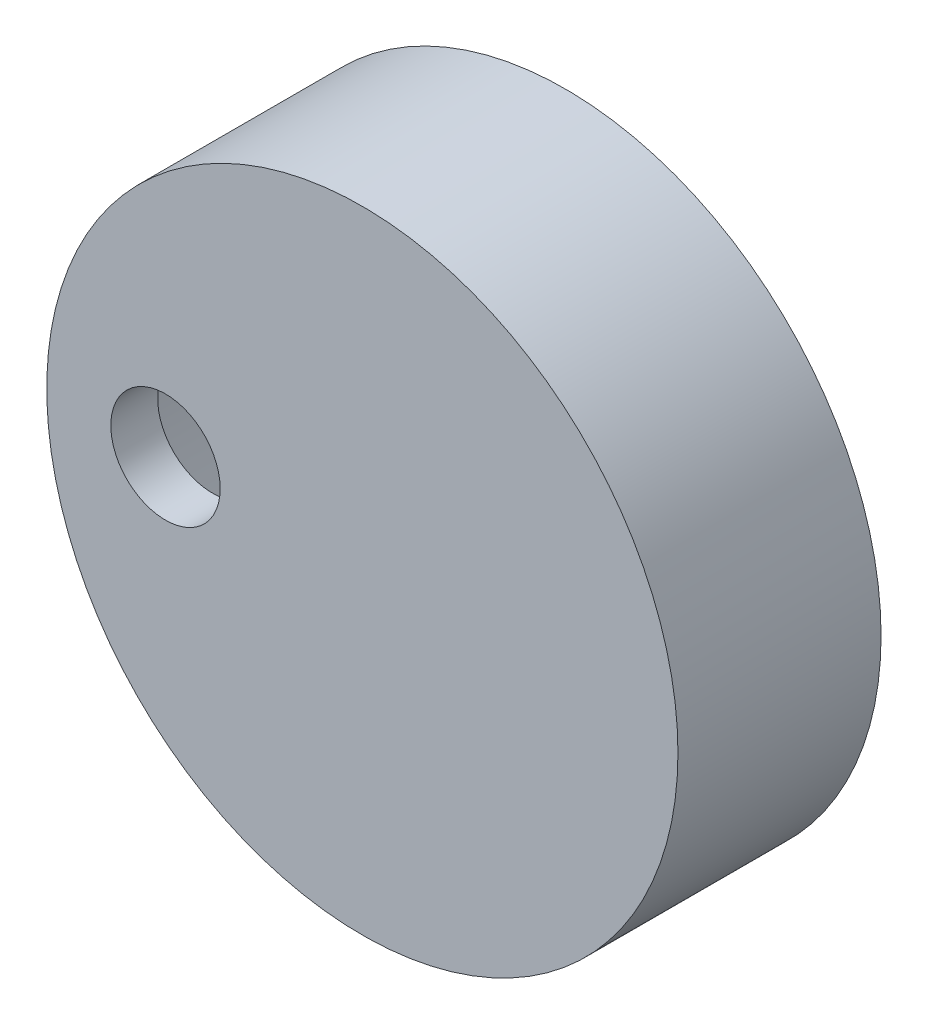
SolidWorks part; units mm, degrees
ref_plane "Front Plane" through (0, 0, 0) normal (0, 0, 1) x (1, 0, 0)
ref_plane "Top Plane" through (0, 0, 0) normal (0, 1, 0) x (1, 0, 0)
ref_plane "Right Plane" through (0, 0, 0) normal (1, 0, 0) x (0, 0, -1)
sketch "Sketch1" plane through (0, 0, 0) normal (0, 0, 1) x (1, 0, 0)
  circle A0 centre (-10.1606, 18.1202) radius 8.6
  circle A1 centre (-10.1606, 18.1202) radius 8.5
  circle A2 centre (-10.1606, 18.1202) radius 8.5 construction
  circle A3 centre (-10.1606, 18.1202) radius 10.1
  dimension "D1" = 0
  dimension "D2" = 0.1
  dimension "D3" = 1.5
extrude "Boss-Extrude1" add sketch "Sketch1" along normal blind 1.5 and the other way blind 5
sketch "Sketch2" plane through (0, 0, 1.5) normal (0, 0, 1) x (1, 0, 0)
  circle A1 centre (-10.1606, 18.1202) radius 10.1
  circle A2 centre (-10.1606, 18.1202) radius 10.1
  dimension "D1" = 0
extrude "Boss-Extrude2" add sketch "Sketch2" against normal blind 1.5 contours A2
sketch "Sketch3" plane through (0, 0, 1.5) normal (0, 0, 1) x (1, 0, 0)
  line L0 (-14.1606, 18.1202) -> (-18.7606, 18.1202) construction
  circle A0 centre (-10.1606, 18.1202) radius 8.6 construction
  circle A1 centre (-10.1606, 18.1202) radius 8.6
  circle A2 centre (-10.1606, 18.1202) radius 4 construction
  circle A3 centre (-10.1606, 18.1202) radius 4
  circle A4 centre (-16.4606, 18.1202) radius 1.75
  dimension "D1" = 3.5
extrude "Cut-Extrude1" cut sketch "Sketch3" against normal blind 1.5 contours A4
